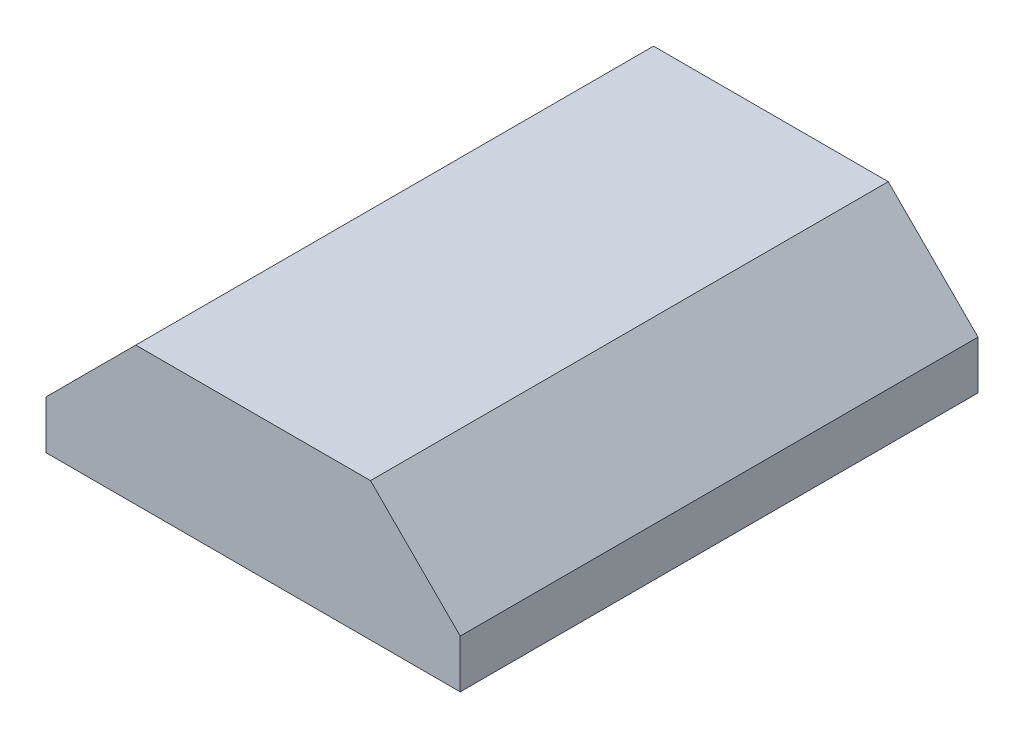
SolidWorks part; units mm, degrees
ref_plane "Ebene vorne" through (0, 0, 0) normal (0, 0, 1) x (1, 0, 0)
ref_plane "Ebene oben" through (0, 0, 0) normal (0, 1, 0) x (1, 0, 0)
ref_plane "Ebene rechts" through (0, 0, 0) normal (1, 0, 0) x (0, 0, -1)
sketch "Skizze1" plane through (0, 0, 0) normal (0, 0, 1) x (1, 0, 0)
  line L0 (0, 0) -> (0, 23680.6173) construction
  line L1 (3.4, 1.8089) -> (-3.4, 1.8089)
  line L2 (-3.4, 1.8089) -> (-6, -0.7911)
  line L3 (-6, -0.7911) -> (-6, -2.1911)
  line L4 (-6, -2.1911) -> (6, -2.1911)
  line L5 (6, -0.7911) -> (6, -2.1911)
  line L6 (3.4, 1.8089) -> (6, -0.7911)
  point P9 (0, -2.1911)
  point P11 (0, 1.8089)
  dimension "D1" = 3.4
  dimension "D2" = 6
  dimension "D3" = 4
  dimension "D4" = 135
extrude "Aufsatz-Linear austragen1" add sketch "Skizze1" along normal blind 15 contours L1 L2 L3 L4 L5 L6
